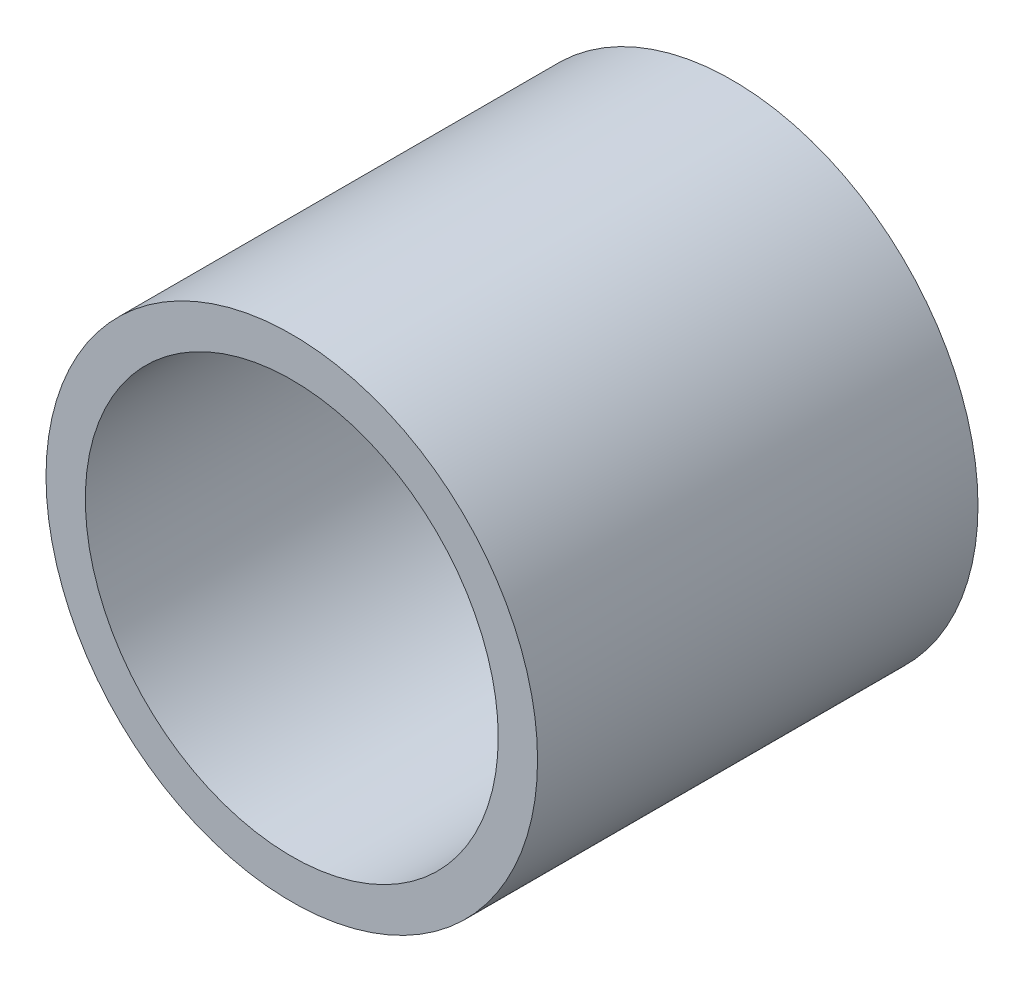
SolidWorks part; units mm, degrees
ref_plane "Front Plane" through (0, 0, 0) normal (0, 0, 1) x (1, 0, 0)
ref_plane "Top Plane" through (0, 0, 0) normal (0, 1, 0) x (1, 0, 0)
ref_plane "Right Plane" through (0, 0, 0) normal (1, 0, 0) x (0, 0, -1)
sketch "Sketch1" plane through (0, 0, 0) normal (0, 0, 1) x (1, 0, 0)
  circle A0 centre (0, 0) radius 15.875
  dimension "D1" = 31.75
extrude "Boss-Extrude1" add sketch "Sketch1" along normal blind 28.448 contours A0
shell "Shell1" thickness 2.54
